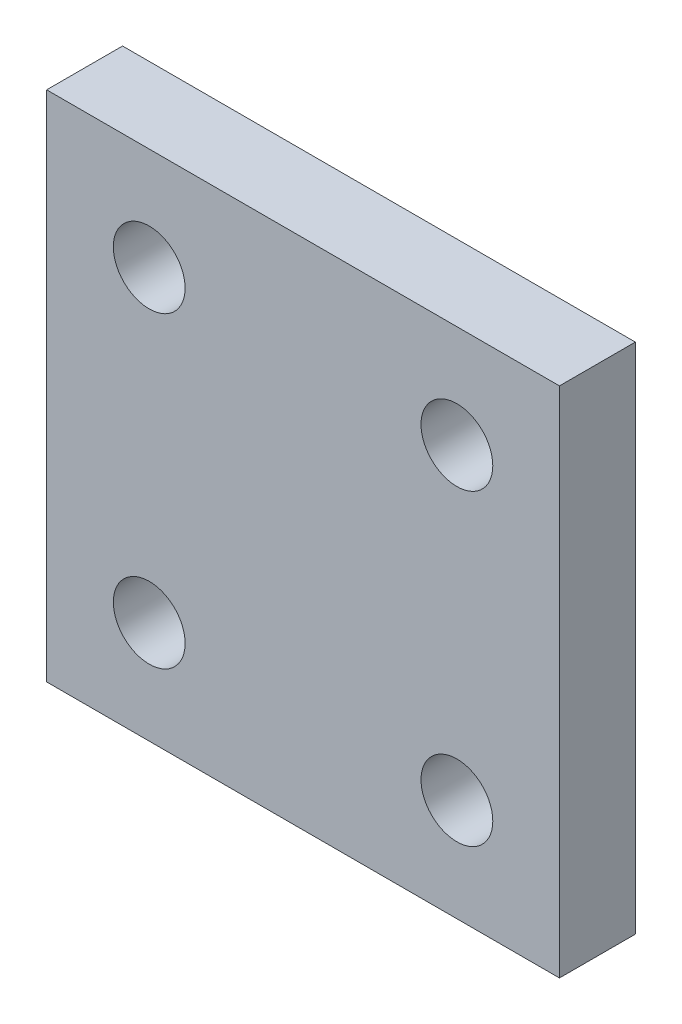
SolidWorks part; units mm, degrees
ref_plane "前视基准面" through (0, 0, 0) normal (0, 0, 1) x (1, 0, 0)
ref_plane "上视基准面" through (0, 0, 0) normal (0, 1, 0) x (1, 0, 0)
ref_plane "右视基准面" through (0, 0, 0) normal (1, 0, 0) x (0, 0, -1)
other "Configuration Table"
sketch "草图1" plane through (0, 0, 0) normal (0, 0, 1) x (1, 0, 0)
  line L1 (0, 0) -> (25, 0)
  line L2 (0, 0) -> (0, 25)
  line L3 (0, 25) -> (25, 25)
  line L4 (25, 0) -> (25, 25)
  dimension "D1" = 25
  dimension "D2" = 25
extrude "凸台-拉伸1" add sketch "草图1" along normal blind 3.7
sketch "草图2" plane through (0, 0, 3.7) normal (0, 0, 1) x (1, 0, 0)
  line L1 (5, 20) -> (20, 20) construction
  line L2 (5, 20) -> (5, 5) construction
  line L3 (5, 5) -> (20, 5) construction
  line L4 (20, 20) -> (20, 5) construction
  line L5 (0, 25) -> (0, 0) construction
  line L6 (25, 25) -> (0, 25) construction
  circle A0 centre (5, 20) radius 1.75
  circle A1 centre (20, 20) radius 1.75
  circle A2 centre (20, 5) radius 1.75
  circle A3 centre (5, 5) radius 1.75
  dimension "D5" = 3.5
  dimension "D1" = 15
  dimension "D2" = 15
  dimension "D3" = 5
  dimension "D4" = 5
extrude "切除-拉伸1" cut sketch "草图2" against normal blind 3.7
